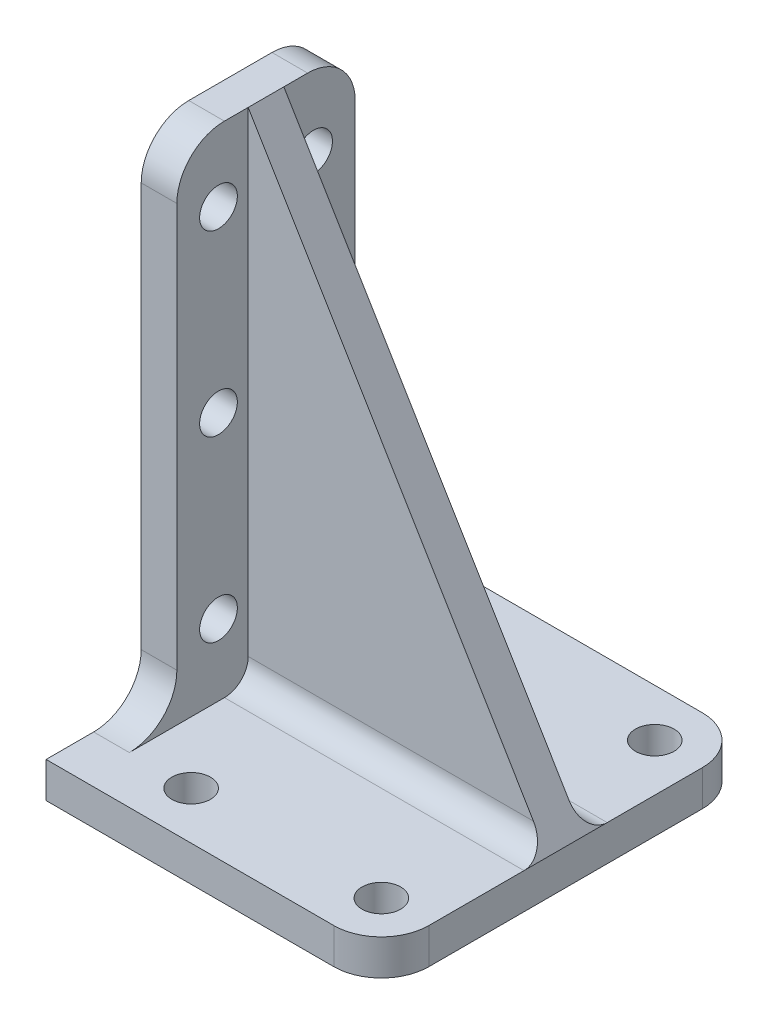
SolidWorks part; units mm, degrees
material "AISI 1020"
ref_plane "Plano frontal" through (0, 0, 0) normal (0, 0, 1) x (1, 0, 0)
ref_plane "Plano superior" through (0, 0, 0) normal (0, 1, 0) x (1, 0, 0)
ref_plane "Plano direito" through (0, 0, 0) normal (1, 0, 0) x (0, 0, -1)
sketch "Esboço1" plane through (0, 0, 0) normal (0, 0, 1) x (1, 0, 0)
  line L0 (0, 0) -> (0, 100)
  line L1 (0, 100) -> (60, 0)
  line L2 (60, 0) -> (0, 0)
  dimension "D1" = 100
  dimension "D2" = 60
extrude "Ressalto-extrusão1" add sketch "Esboço1" along normal blind 30
ref_plane "Plano1" through (6, 0, 0) normal (-1, 0, 0) x (0, 0, 1)
sketch "Esboço2" plane through (6, 0, 0) normal (-1, 0, 0) x (0, 0, 1)
  line L0 (30, 100) -> (0, 100) construction
  line L1 (18, 100) -> (30, 100)
  line L2 (18, 100) -> (18, 6)
  line L3 (18, 6) -> (30, 6)
  line L4 (30, 100) -> (30, 6)
  line L5 (0, 0) -> (0, 100) construction
  line L6 (12, 100) -> (0, 100)
  line L7 (12, 100) -> (12, 6)
  line L8 (12, 6) -> (0, 6)
  line L9 (0, 100) -> (0, 6)
  line L10 (30, 0) -> (0, 0) construction
  line L11 (30, 0) -> (30, 100) construction
  line L12 (18, 6) -> (12, 6) construction
  line L13 (15, 6) -> (15, 0) construction
  dimension "D1" = 6
  dimension "D2" = 6
extrude "Corte-extrusão1" cut sketch "Esboço2" against normal through all
sketch "Esboço3" plane through (6, 0, 0) normal (1, 0, 0) x (0, 0, -1)
  line L1 (-30, 90) -> (0, 90)
  line L2 (-30, 90) -> (-30, 100)
  line L3 (-30, 100) -> (0, 100)
  line L4 (0, 90) -> (0, 100)
extrude "Corte-extrusão2" cut sketch "Esboço3" against normal through all
sketch "Esboço4" plane through (0, 6, 0) normal (0, 1, 0) x (1, 0, 0)
  line L1 (56.4, 0) -> (60, 0)
  line L2 (56.4, 0) -> (56.4, -30)
  line L3 (56.4, -30) -> (60, -30)
  line L4 (60, 0) -> (60, -30)
extrude "Corte-extrusão3" cut sketch "Esboço4" against normal through all
sketch "Esboço5" plane through (0, 0, 30) normal (0, 0, 1) x (1, 0, 0)
  line L1 (56.4, 6) -> (0, 6)
  line L2 (56.4, 6) -> (56.4, 0)
  line L3 (56.4, 0) -> (0, 0)
  line L4 (0, 6) -> (0, 0)
extrude "Ressalto-extrusão2" add sketch "Esboço5" along normal blind 16
sketch "Esboço6" plane through (0, 0, 0) normal (0, 0, -1) x (-1, 0, 0)
  line L1 (-56.4, 6) -> (0, 6)
  line L2 (-56.4, 6) -> (-56.4, 0)
  line L3 (-56.4, 0) -> (0, 0)
  line L4 (0, 6) -> (0, 0)
extrude "Ressalto-extrusão3" add sketch "Esboço6" along normal blind 16
fillet "Filete1" radius 8 2 edges at (3, 6, 30) (3, 6, 0)
fillet "Filete2" radius 8 2 edges at (56.4, 3, -16) (56.4, 3, 46)
fillet "Filete3" radius 8 2 edges at (3, 90, 30) (3, 90, 0)
fillet "Filete4" radius 4 2 edges at (31.2, 6, 18) (31.2, 6, 12)
sketch "Esboço7" plane through (6, 0, 0) normal (1, 0, 0) x (0, 0, -1)
  line L0 (-15, 90) -> (-15, 0) construction
  line L1 (-18, 90) -> (-12, 90) construction
  line L2 (8, 0) -> (-38, 0) construction
  line L3 (-22, 90) -> (-18, 90) construction
  circle A0 centre (-23, 78) radius 3.175
  circle A1 centre (-23, 48) radius 3.175
  circle A2 centre (-23, 18) radius 3.175
  circle A3 centre (-7, 18) radius 3.175
  circle A4 centre (-7, 48) radius 3.175
  circle A5 centre (-7, 78) radius 3.175
  dimension "D1" = 30
  dimension "D2" = 30
  dimension "D4" = 6.35
  dimension "D5" = 12
  dimension "D3" = 8
extrude "Corte-extrusão4" cut sketch "Esboço7" against normal through all
sketch "Esboço8" plane through (0, 6, 0) normal (0, 1, 0) x (1, 0, 0)
  line L0 (48.4, -15) -> (56.4, -15) construction
  line L1 (16.4, 8) -> (48.4, 8) construction
  line L2 (16.4, 8) -> (16.4, -38) construction
  line L3 (16.4, -38) -> (48.4, -38) construction
  line L4 (48.4, 8) -> (48.4, -38) construction
  line L5 (56.4, -8) -> (56.4, -22) construction
  circle A0 centre (48.4, 8) radius 3.25
  circle A1 centre (48.4, -38) radius 3.25
  circle A2 centre (16.4, -38) radius 3.25
  circle A3 centre (16.4, 8) radius 3.25
  dimension "D4" = 6.5
  dimension "D1" = 8
  dimension "D2" = 32
  dimension "D3" = 46
extrude "Corte-extrusão5" cut sketch "Esboço8" against normal through all
